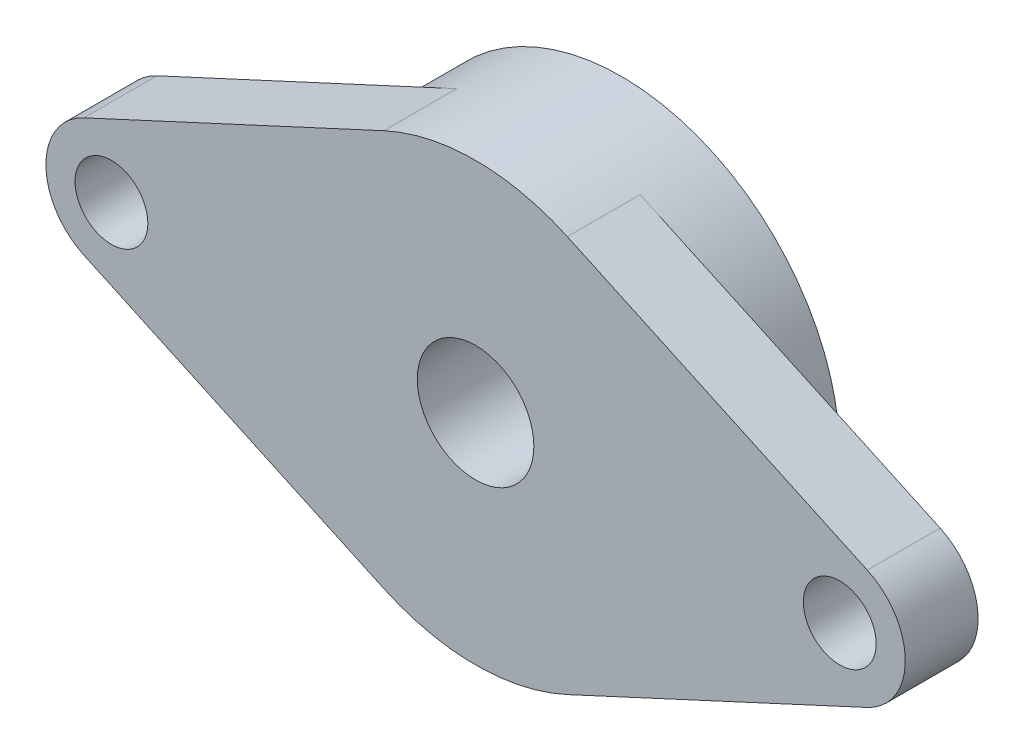
SolidWorks part; units mm, degrees
ref_plane "Front Plane" through (0, 0, 0) normal (0, 0, 1) x (1, 0, 0)
ref_plane "Top Plane" through (0, 0, 0) normal (0, 1, 0) x (1, 0, 0)
ref_plane "Right Plane" through (0, 0, 0) normal (1, 0, 0) x (0, 0, -1)
sketch "Sketch1" plane through (0, 0, 0) normal (0, 0, 1) x (1, 0, 0)
  line L0 (-27.5, 0) -> (56.6229, 0) construction
  line L1 (0, 26.1337) -> (0, -45.2983) construction
  line L2 (26.89, -4.0839) -> (6.3, -13.6129)
  line L3 (-26.89, -4.0839) -> (-6.3, -13.6129)
  line L4 (-26.89, 4.0839) -> (-6.3, 13.6129)
  line L5 (26.89, 4.0839) -> (6.3, 13.6129)
  circle A0 centre (0, 0) radius 4
  circle A1 centre (0, 0) radius 15
  circle A2 centre (-25, 0) radius 2.5
  circle A3 centre (25, 0) radius 2.5
  circle A4 centre (25, 0) radius 4.5
  circle A5 centre (-25, 0) radius 4.5
  dimension "D1" = 8
  dimension "D2" = 30
  dimension "D3" = 5
  dimension "D4" = 25
  dimension "D5" = 2
extrude "Boss-Extrude1" add sketch "Sketch1" along normal blind 5
sketch "Sketch2" plane through (0, 0, 0) normal (0, 0, -1) x (-1, 0, 0)
  circle A0 centre (0, 0) radius 15
  circle A1 centre (0, 0) radius 4
  dimension "D1" = 8
extrude "Boss-Extrude2" add sketch "Sketch2" along normal blind 5
